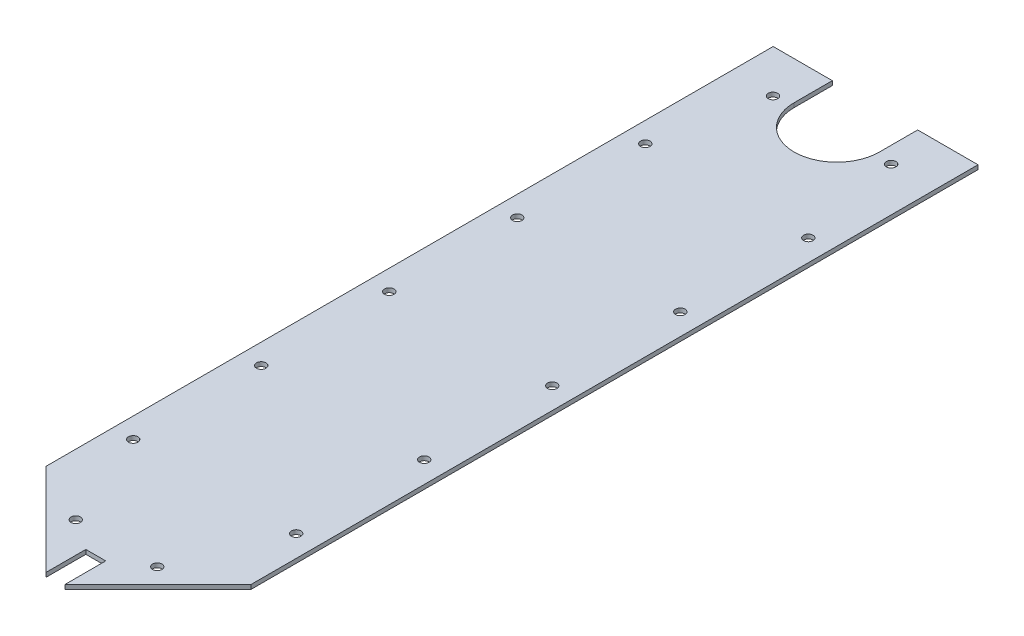
SolidWorks part; units mm, degrees
material "6061-T6 (SS)"
ref_plane "Front Plane" through (0, 0, 0) normal (0, 0, 1) x (1, 0, 0)
ref_plane "Top Plane" through (0, 0, 0) normal (0, 1, 0) x (1, 0, 0)
ref_plane "Right Plane" through (0, 0, 0) normal (1, 0, 0) x (0, 0, -1)
sketch "Sketch3" plane through (0, 0, 0) normal (0, 1, 0) x (1, 0, 0)
  line L0 (-71.592, 291.8005) -> (-30.0058, 291.8005)
  line L3 (30.0058, 291.8005) -> (72.4083, 291.8005)
  line L4 (-30.0058, 264.9348) -> (-30.0058, 291.8005)
  line L5 (30.0058, 264.9348) -> (30.0058, 291.8005)
  line L8 (-71.592, 291.8005) -> (-71.592, -219.3734)
  line L9 (-71.592, -219.3734) -> (0.4081, -291.3736)
  line L10 (0.4081, -291.3736) -> (72.4083, -219.3734)
  line L11 (72.4083, -219.3734) -> (72.4083, 291.8005)
  arc A1 (-30.0058, 264.9348) -> (30.0058, 264.9348) centre (0, 264.9348) ccw
  dimension "D2" = 30.0058
  dimension "D1" = 0.4081
  dimension "D3" = 264.9348
  dimension "D4" = 72.4083
  dimension "D5" = 291.8005
  dimension "D8" = 219.3734
extrude "Boss-Extrude2" add sketch "Sketch3" along normal blind 3
sketch "Sketch4" plane through (0, 3, 0) normal (0, 1, 0) x (1, 0, 0)
  line L7 (-7, -283.9654) -> (-7, -255.9654)
  line L8 (-71.592, -219.3734) -> (0.4081, -291.3736) construction
  line L10 (7, -255.9654) -> (7, -284.7817)
  line L11 (0.4081, -291.3736) -> (72.4083, -219.3734) construction
  line L12 (-7, -283.9654) -> (0.4081, -291.3736)
  line L13 (0.4081, -291.3736) -> (7, -284.7817)
  line L14 (-71.592, 291.8005) -> (-71.592, -219.3734) construction
  line L17 (-7, -255.9654) -> (7, -255.9654)
  dimension "D1" = 14
  dimension "D2" = 28
  dimension "D3" = 64.592
extrude "Cut-Extrude1" cut sketch "Sketch4" against normal through all
sketch "Sketch5" plane through (0, 3, 0) normal (0, 1, 0) x (1, 0, 0)
  line L0 (-7, -283.9654) -> (-28.6501, -283.9654) construction
  line L1 (-28.6501, -283.9654) -> (-28.6501, -241.4151) construction
  line L2 (0, 291.8758) -> (0, -294.8294) construction
  line L5 (-7, -255.9654) -> (-7, -283.9654) construction
  circle A0 centre (-28.6501, -241.4151) radius 3.325
  circle A2 centre (-57.3002, -172.3727) radius 3.325
  circle A3 centre (-57.3002, -82.3727) radius 3.325
  circle A4 centre (-57.3002, 7.6273) radius 3.325
  circle A6 centre (-57.3002, 97.6273) radius 3.325
  circle A7 centre (-57.3002, 187.6273) radius 3.325
  circle A10 centre (57.3002, 187.6273) radius 3.325
  circle A12 centre (57.3002, 97.6273) radius 3.325
  circle A14 centre (57.3002, -82.3727) radius 3.325
  circle A15 centre (57.3002, -172.3727) radius 3.325
  circle A16 centre (57.3002, 7.6273) radius 3.325
  circle A17 centre (28.6501, -241.4151) radius 3.325
  circle A18 centre (41.5373, 261.6098) radius 3.325
  circle A19 centre (-41.5373, 261.6098) radius 3.325
  dimension "D3" = 35.6501
  dimension "D4" = 48.5373
  dimension "D9" = 47.0007
  dimension "D1" = 6.65
  dimension "D2" = 7
  dimension "D5" = 64.3002
  dimension "D6" = 21.6501
  dimension "D7" = 34.5373
  dimension "D8" = 50.3002
  dimension "D10" = 137.0007
  dimension "D11" = 227.0007
  dimension "D12" = 317.0007
  dimension "D13" = 407.0007
  dimension "D14" = 480.9832
  dimension "D15" = 22.0417
  dimension "D16" = 64.592
  dimension "D17" = 575.8412
  dimension "D18" = 294.8294
  dimension "D19" = 21.6501
extrude "Cut-Extrude2" cut sketch "Sketch5" against normal through all both
